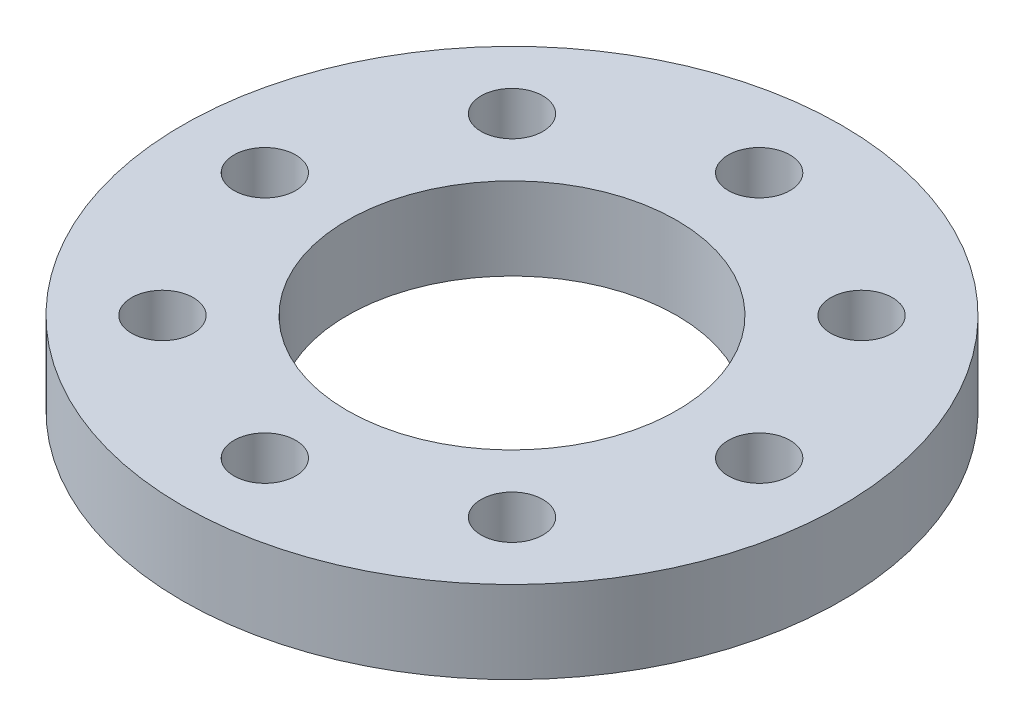
SolidWorks part; units mm, degrees
material "Cast Carbon Steel"
ref_plane "Front Plane" through (0, 0, 0) normal (0, 0, 1) x (1, 0, 0)
ref_plane "Top Plane" through (0, 0, 0) normal (0, 1, 0) x (1, 0, 0)
ref_plane "Right Plane" through (0, 0, 0) normal (1, 0, 0) x (0, 0, -1)
sketch "Sketch1" plane through (0, 0, 0) normal (0, 1, 0) x (1, 0, 0)
  circle A0 centre (0, 0) radius 203.2
  circle A1 centre (0, 0) radius 101.6
  arc A2 (19.0128, 151.2094) -> (-19.0128, 151.2094) centre (0, 0) ccw
  circle A3 centre (0, 152.4) radius 19.05
  circle A4 centre (107.7631, 107.7631) radius 19.05
  circle A5 centre (152.4, 0) radius 19.05
  circle A6 centre (107.7631, -107.7631) radius 19.05
  circle A7 centre (0, -152.4) radius 19.05
  circle A8 centre (-107.7631, -107.7631) radius 19.05
  circle A9 centre (-152.4, 0) radius 19.05
  circle A10 centre (-107.7631, 107.7631) radius 19.05
  point P24 (0, 0)
  dimension "D1" = 406.4
  dimension "D2" = 203.2
  dimension "D3" = 304.8
  dimension "D4" = 38.1
  dimension "D5" = 8
extrude "Boss-Extrude1" add sketch "Sketch1" along normal blind 50.8 contours A0 A10 A9 A8 A7 A6 A5 A4 A3 A1
